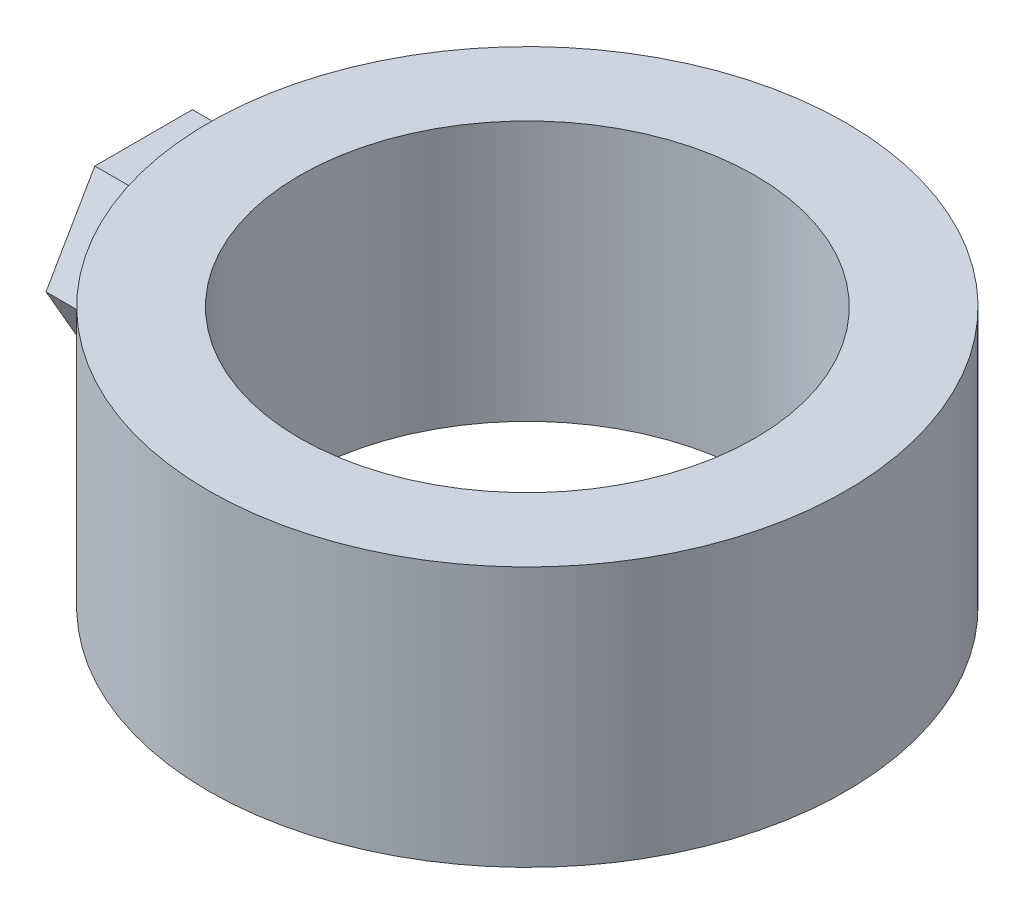
SolidWorks part; units mm, degrees
ref_plane "Спереди (XY)" through (0, 0, 0) normal (0, 0, 1) x (1, 0, 0)
ref_plane "Сверху (XZ)" through (0, 0, 0) normal (0, 1, 0) x (1, 0, 0)
ref_plane "Справа (ZY)" through (0, 0, 0) normal (1, 0, 0) x (0, 0, -1)
sketch "Эскиз2" plane through (0, 0, 0) normal (0, 1, 0) x (1, 0, 0)
  circle A0 centre (0, 0) radius 17.5
  circle A1 centre (0, 0) radius 24.5
  dimension "D1" = 35
  dimension "D2" = 7
extrude "Бобышка-Вытянуть1" add sketch "Эскиз2" along normal mid plane 20
sketch "Эскиз3" plane through (0, 0, 0) normal (1, 0, 0) x (0, 0, -1)
  line L1 (7.5056, 0) -> (3.7528, 6.5)
  line L2 (3.7528, 6.5) -> (-3.7528, 6.5)
  line L3 (-3.7528, 6.5) -> (-7.5056, 0)
  line L4 (-7.5056, 0) -> (-3.7528, -6.5)
  line L5 (-3.7528, -6.5) -> (3.7528, -6.5)
  line L6 (3.7528, -6.5) -> (7.5056, 0)
  circle A0 centre (0, 0) radius 6.5 construction
  dimension "D1" = 13
extrude "Бобышка-Вытянуть2" add sketch "Эскиз3" against normal blind 9.5 from offset 20 offset against normal yes
sketch "Эскиз4" plane through (-29.5, 0, 0) normal (-1, 0, 0) x (0, 0, 1)
  circle A0 centre (0, 0) radius 4
  dimension "D1" = 8
extrude "Вырез-Вытянуть2" cut sketch "Эскиз4" against normal blind 5
